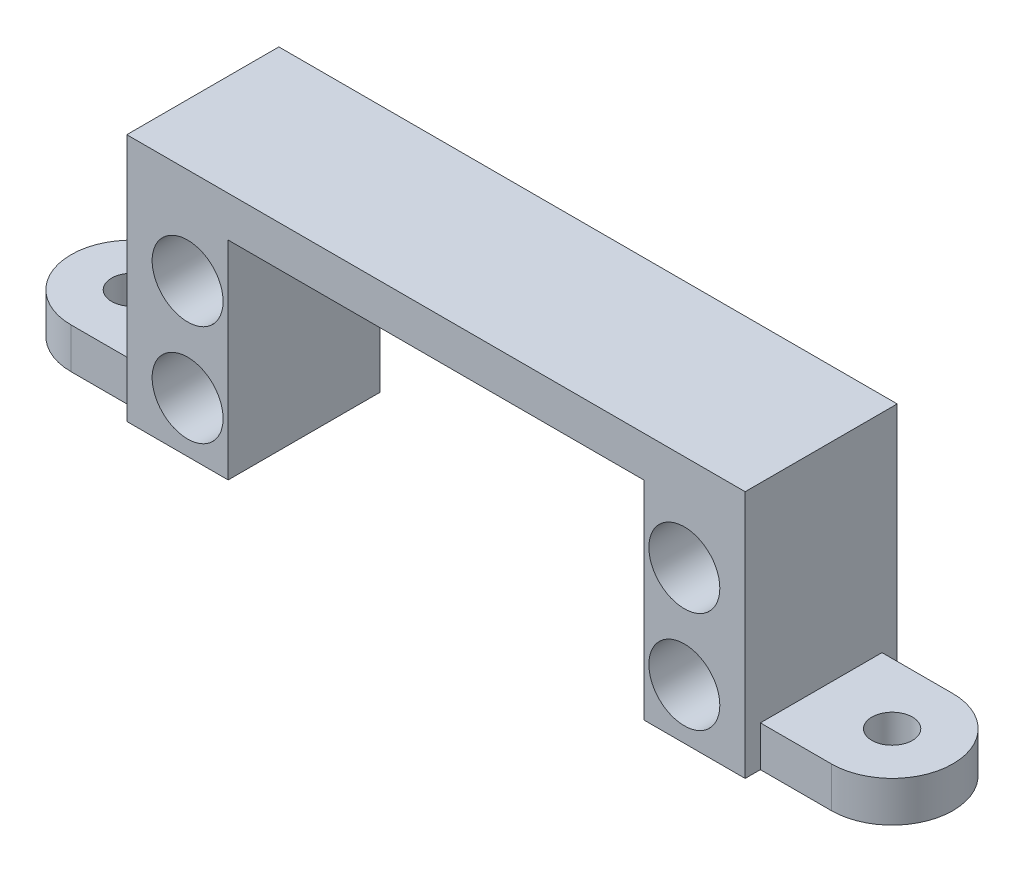
SolidWorks part; units mm, degrees
ref_plane "Front Plane" through (0, 0, 0) normal (0, 0, 1) x (1, 0, 0)
ref_plane "Top Plane" through (0, 0, 0) normal (0, 1, 0) x (1, 0, 0)
ref_plane "Right Plane" through (0, 0, 0) normal (1, 0, 0) x (0, 0, -1)
sketch "Sketch1" plane through (0, 0, 0) normal (0, 0, 1) x (1, 0, 0)
  line L12 (0, 0) -> (0, 20.5)
  line L13 (0, 20.5) -> (41, 20.5)
  line L14 (41, 20.5) -> (41, 0)
  line L15 (41, 0) -> (51, 0)
  line L16 (51, 0) -> (51, 24.5)
  line L17 (51, 24.5) -> (-10, 24.5)
  line L18 (-10, 24.5) -> (-10, 0)
  line L19 (-10, 0) -> (0, 0)
  dimension "D1" = 10
  dimension "D2" = 20.5
  dimension "D3" = 4
  dimension "D4" = 41
  dimension "D5" = 10
extrude "Boss-Extrude1" add sketch "Sketch1" along normal blind 15
sketch "Sketch2" plane through (0, 0, 15) normal (0, 0, 1) x (1, 0, 0)
  line L0 (-10, 0) -> (0, 0) construction
  line L1 (0, 0) -> (0, 20.5) construction
  line L2 (41, 0) -> (51, 0) construction
  line L3 (41, 20.5) -> (41, 0) construction
  circle A0 centre (45, 5) radius 3.5
  circle A1 centre (45, 15) radius 3.5
  circle A2 centre (-4, 5) radius 3.5
  circle A3 centre (-4, 15) radius 3.5
  dimension "D1" = 7
  dimension "D2" = 7
  dimension "D3" = 7
  dimension "D4" = 7
  dimension "D5" = 5
  dimension "D6" = 4
  dimension "D7" = 4
  dimension "D8" = 10
  dimension "D9" = 5
  dimension "D10" = 4
  dimension "D11" = 4
  dimension "D12" = 10
extrude "Cut-Extrude1" cut sketch "Sketch2" against normal offset from surface (11 mm away) 4 up to face at (20.5, 11.25, 0)
sketch "Sketch3" plane through (0, 0, 4) normal (0, 0, 1) x (1, 0, 0)
  circle A0 centre (-4, 15) radius 2
  circle A1 centre (-4, 5) radius 2
  circle A2 centre (45, 15) radius 2
  circle A3 centre (45, 5) radius 2
  dimension "D1" = 4
  dimension "D2" = 4
  dimension "D3" = 4
  dimension "D4" = 4
extrude "Cut-Extrude2" cut sketch "Sketch3" against normal up to next
sketch "Sketch4" plane through (0, 0, 0) normal (0, -1, 0) x (1, 0, 0)
  line L0 (-10, 7.5) -> (-17, 7.5) construction
  line L1 (-10, 15) -> (-10, 0) construction
  line L2 (58, 7.5) -> (51, 7.5) construction
  line L3 (51, 15) -> (51, 0) construction
  line L4 (58, 13.5) -> (51, 13.5)
  line L5 (58, 1.5) -> (51, 1.5)
  line L6 (-17, 13.5) -> (-10, 13.5)
  line L7 (-17, 1.5) -> (-15.4251, 1.7104)
  line L8 (-17, 1.5) -> (-10, 1.5)
  line L9 (-10, 13.5) -> (-10, 1.5)
  line L10 (51, 13.5) -> (51, 1.5)
  circle A0 centre (-17, 7.5) radius 2
  circle A1 centre (58, 7.5) radius 2
  circle A2 centre (-17, 7.5) radius 6
  circle A3 centre (58, 7.5) radius 6
  line M10 (-10, 15) -> (-10, 0)
  dimension "D1" = 4
  dimension "D2" = 4
  dimension "D3" = 4
  dimension "D4" = 4
  dimension "D5" = 7
  dimension "D6" = 7
extrude "Boss-Extrude5" add sketch "Sketch4" against normal blind 4 contours A3 A1 | A3 L4 L10 L5 | A2 L8 L6 M10 | A0
